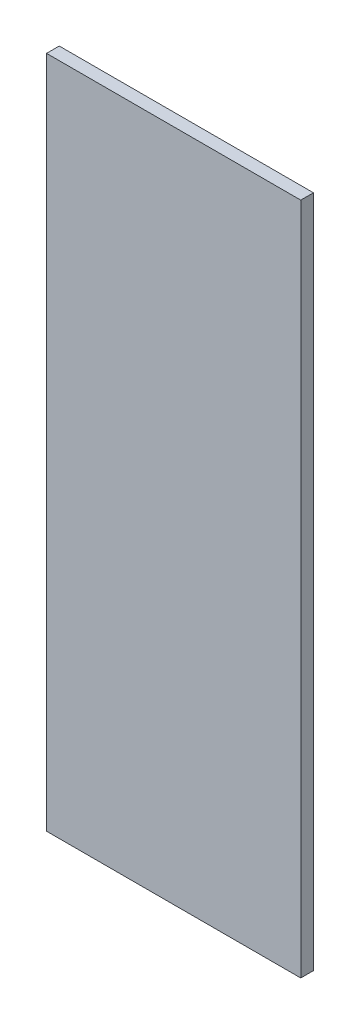
SolidWorks part; units mm, degrees
ref_plane "Alzado" through (0, 0, 0) normal (0, 0, 1) x (1, 0, 0)
ref_plane "Planta" through (0, 0, 0) normal (0, 1, 0) x (1, 0, 0)
ref_plane "Vista lateral" through (0, 0, 0) normal (1, 0, 0) x (0, 0, -1)
sketch "Croquis1" plane through (0, 0, 0) normal (0, 0, 1) x (1, 0, 0)
  line L1 (0, 0) -> (80, 0)
  line L2 (0, 0) -> (0, 212)
  line L3 (0, 212) -> (80, 212)
  line L4 (80, 0) -> (80, 212)
  dimension "D1" = 212
  dimension "D2" = 80
extrude "Saliente-Extruir1" add sketch "Croquis1" along normal blind 4
